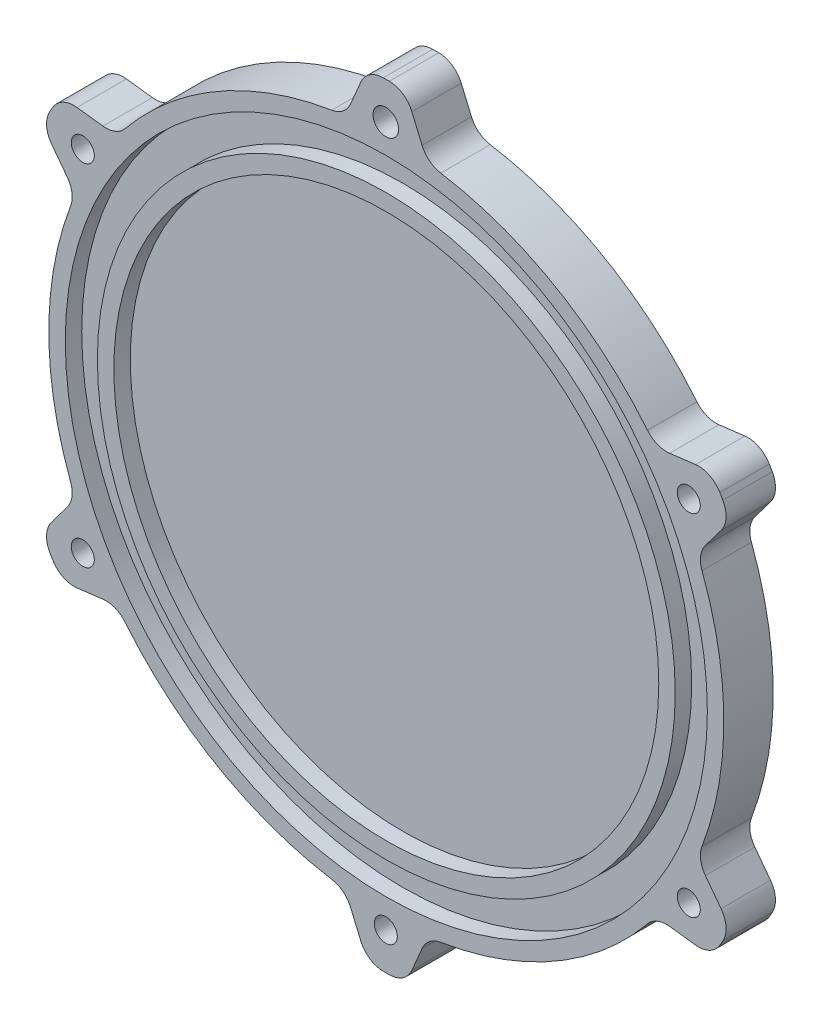
SolidWorks part; units mm, degrees
material "6063-O"
ref_plane "Front Plane" through (0, 0, 0) normal (0, 0, 1) x (1, 0, 0)
ref_plane "Top Plane" through (0, 0, 0) normal (0, 1, 0) x (1, 0, 0)
ref_plane "Right Plane" through (0, 0, 0) normal (1, 0, 0) x (0, 0, -1)
sketch "Sketch1" plane through (0, 0, 0) normal (0, 0, 1) x (1, 0, 0)
  line L0 (21.3582, 60.1994) -> (21.3582, 72.0387)
  line L1 (-3.1055, 45.1702) -> (-4.344, 42.2509)
  line L2 (3.1055, 45.1702) -> (4.344, 42.2509)
  line L3 (37.5658, 25.2746) -> (34.4183, 24.8874)
  line L4 (40.6713, 19.8956) -> (38.7623, 17.3635)
  line L5 (40.6713, -19.8956) -> (38.7623, -17.3635)
  line L6 (37.5658, -25.2746) -> (34.4183, -24.8874)
  line L7 (3.1055, -45.1702) -> (4.344, -42.2509)
  line L8 (-3.1055, -45.1702) -> (-4.344, -42.2509)
  line L9 (-37.5658, -25.2746) -> (-34.4183, -24.8874)
  line L10 (-40.6713, -19.8956) -> (-38.7623, -17.3635)
  line L11 (-40.6713, 19.8956) -> (-38.7623, 17.3635)
  line L12 (-37.5658, 25.2746) -> (-34.4183, 24.8874)
  arc A0 (40.8855, 23.1813) -> (40.5184, 23.8173) centre (0, 0) ccw
  arc A1 (-6.6213, 40.4618) -> (-31.7303, 25.9651) centre (0, 0) ccw
  arc A2 (0.3672, 46.9986) -> (-0.3672, 46.9986) centre (0, 0) ccw
  arc A3 (3.1055, 45.1702) -> (0.3672, 46.9986) centre (0.3438, 43.9987) ccw
  arc A4 (-0.3672, 46.9986) -> (-3.1055, 45.1702) centre (-0.3438, 43.9987) ccw
  arc A5 (6.6213, 40.4618) -> (4.344, 42.2509) centre (7.1057, 43.4224) cw
  arc A6 (-6.6213, 40.4618) -> (-4.344, 42.2509) centre (-7.1057, 43.4224) ccw
  arc A7 (40.6713, 19.8956) -> (40.8855, 23.1813) centre (38.2758, 21.7016) ccw
  arc A8 (40.5184, 23.8173) -> (37.5658, 25.2746) centre (37.9321, 22.297) ccw
  arc A9 (38.3516, 14.4967) -> (38.7623, 17.3635) centre (41.1578, 15.5575) cw
  arc A10 (31.7303, 25.9651) -> (34.4183, 24.8874) centre (34.0521, 27.865) ccw
  arc A11 (31.7303, 25.9651) -> (6.6213, 40.4618) centre (0, 0) ccw
  arc A12 (40.5184, -23.8173) -> (40.8855, -23.1813) centre (0, 0) ccw
  arc A13 (37.5658, -25.2746) -> (40.5184, -23.8173) centre (37.9321, -22.297) ccw
  arc A14 (40.8855, -23.1813) -> (40.6713, -19.8956) centre (38.2758, -21.7016) ccw
  arc A15 (31.7303, -25.9651) -> (34.4183, -24.8874) centre (34.0521, -27.865) cw
  arc A16 (38.3516, -14.4967) -> (38.7623, -17.3635) centre (41.1578, -15.5575) ccw
  arc A17 (38.3516, -14.4967) -> (38.3516, 14.4967) centre (0, 0) ccw
  arc A18 (-0.3672, -46.9986) -> (0.3672, -46.9986) centre (0, 0) ccw
  arc A19 (-3.1055, -45.1702) -> (-0.3672, -46.9986) centre (-0.3438, -43.9987) ccw
  arc A20 (0.3672, -46.9986) -> (3.1055, -45.1702) centre (0.3438, -43.9987) ccw
  arc A21 (-6.6213, -40.4618) -> (-4.344, -42.2509) centre (-7.1057, -43.4224) cw
  arc A22 (6.6213, -40.4618) -> (4.344, -42.2509) centre (7.1057, -43.4224) ccw
  arc A23 (6.6213, -40.4618) -> (31.7303, -25.9651) centre (0, 0) ccw
  arc A24 (-40.8855, -23.1813) -> (-40.5184, -23.8173) centre (0, 0) ccw
  arc A25 (-40.6713, -19.8956) -> (-40.8855, -23.1813) centre (-38.2758, -21.7016) ccw
  arc A26 (-40.5184, -23.8173) -> (-37.5658, -25.2746) centre (-37.9321, -22.297) ccw
  arc A27 (-38.3516, -14.4967) -> (-38.7623, -17.3635) centre (-41.1578, -15.5575) cw
  arc A28 (-31.7303, -25.9651) -> (-34.4183, -24.8874) centre (-34.0521, -27.865) ccw
  arc A29 (-31.7303, -25.9651) -> (-6.6213, -40.4618) centre (0, 0) ccw
  arc A30 (-40.5184, 23.8173) -> (-40.8855, 23.1813) centre (0, 0) ccw
  arc A31 (-37.5658, 25.2746) -> (-40.5184, 23.8173) centre (-37.9321, 22.297) ccw
  arc A32 (-40.8855, 23.1813) -> (-40.6713, 19.8956) centre (-38.2758, 21.7016) ccw
  arc A33 (-31.7303, 25.9651) -> (-34.4183, 24.8874) centre (-34.0521, 27.865) cw
  arc A34 (-38.3516, 14.4967) -> (-38.7623, 17.3635) centre (-41.1578, 15.5575) ccw
  arc A35 (-38.3516, 14.4967) -> (-38.3516, -14.4967) centre (0, 0) ccw
  arc A36 (-38.3516, 14.4967) -> (-38.3516, -14.4967) centre (0, 0) ccw
  arc A37 (-38.3516, 14.4967) -> (-38.3516, -14.4967) centre (0, 0) ccw
  arc A38 (-38.3516, 14.4967) -> (-38.3516, -14.4967) centre (0, 0) ccw
  arc A39 (-38.3516, 14.4967) -> (-38.3516, -14.4967) centre (0, 0) ccw
  arc A40 (-38.3516, 14.4967) -> (-38.3516, -14.4967) centre (0, 0) ccw
  arc A41 (-31.7303, -25.9651) -> (-6.6213, -40.4618) centre (0, 0) ccw
  arc A42 (-31.7303, -25.9651) -> (-6.6213, -40.4618) centre (0, 0) ccw
  arc A43 (-31.7303, -25.9651) -> (-6.6213, -40.4618) centre (0, 0) ccw
  arc A44 (-31.7303, -25.9651) -> (-6.6213, -40.4618) centre (0, 0) ccw
  arc A45 (-31.7303, -25.9651) -> (-6.6213, -40.4618) centre (0, 0) ccw
  arc A46 (6.6213, -40.4618) -> (31.7303, -25.9651) centre (0, 0) ccw
  arc A47 (6.6213, -40.4618) -> (31.7303, -25.9651) centre (0, 0) ccw
  arc A48 (6.6213, -40.4618) -> (31.7303, -25.9651) centre (0, 0) ccw
  arc A49 (6.6213, -40.4618) -> (31.7303, -25.9651) centre (0, 0) ccw
  arc A50 (6.6213, -40.4618) -> (31.7303, -25.9651) centre (0, 0) ccw
  arc A51 (31.7303, 25.9651) -> (6.6213, 40.4618) centre (0, 0) ccw
  arc A52 (31.7303, 25.9651) -> (6.6213, 40.4618) centre (0, 0) ccw
  arc A53 (31.7303, 25.9651) -> (6.6213, 40.4618) centre (0, 0) ccw
  arc A54 (31.7303, 25.9651) -> (6.6213, 40.4618) centre (0, 0) ccw
  arc A55 (31.7303, 25.9651) -> (6.6213, 40.4618) centre (0, 0) ccw
  arc A56 (38.3516, -14.4967) -> (38.3516, 14.4967) centre (0, 0) ccw
  arc A57 (38.3516, -14.4967) -> (38.3516, 14.4967) centre (0, 0) ccw
  arc A58 (38.3516, -14.4967) -> (38.3516, 14.4967) centre (0, 0) ccw
  arc A59 (38.3516, -14.4967) -> (38.3516, 14.4967) centre (0, 0) ccw
  arc A60 (38.3516, -14.4967) -> (38.3516, 14.4967) centre (0, 0) ccw
  arc A61 (-6.6213, 40.4618) -> (-31.7303, 25.9651) centre (0, 0) ccw
  arc A62 (-6.6213, 40.4618) -> (-31.7303, 25.9651) centre (0, 0) ccw
  arc A63 (-6.6213, 40.4618) -> (-31.7303, 25.9651) centre (0, 0) ccw
  arc A64 (-6.6213, 40.4618) -> (-31.7303, 25.9651) centre (0, 0) ccw
  arc A65 (-6.6213, 40.4618) -> (-31.7303, 25.9651) centre (0, 0) ccw
  circle A66 centre (-0.0635, 42.5) radius 1.55
  circle A67 centre (36.7426, 21.25) radius 1.4
  circle A68 centre (36.7426, -21.25) radius 1.4
  circle A69 centre (-0.0635, -42.5) radius 1.4
  circle A70 centre (-36.8696, -21.25) radius 1.4
  circle A71 centre (-36.8696, 21.25) radius 1.4
  point P76 (0, 0)
  point P88 (-0.0635, 0)
extrude "Boss-Extrude1" add sketch "Sketch1" along normal blind 6 contours A34 A35 A27 L10 A25 A24 A26 L9 A28 A29 A21 L8 A19 A18 A20 L7 A22 A23 A15 L6 A13 A12 A14 L5 A16 A17 A9 L4 A7 A0 A8 L3 A10 A11 A5 L2 A3 A2 A4 L1 A6 A1 A33 L12 A31 A30 A32 L11 A71
sketch "Sketch2" plane through (0, 0, 6) normal (0, 0, 1) x (1, 0, 0)
  circle A0 centre (0, 0) radius 35.1
  circle A1 centre (0, 0) radius 39
  circle A2 centre (0, 0) radius 33.1
extrude "Cut-Extrude1" cut sketch "Sketch2" against normal blind 2 contours A1 A0 | A2
